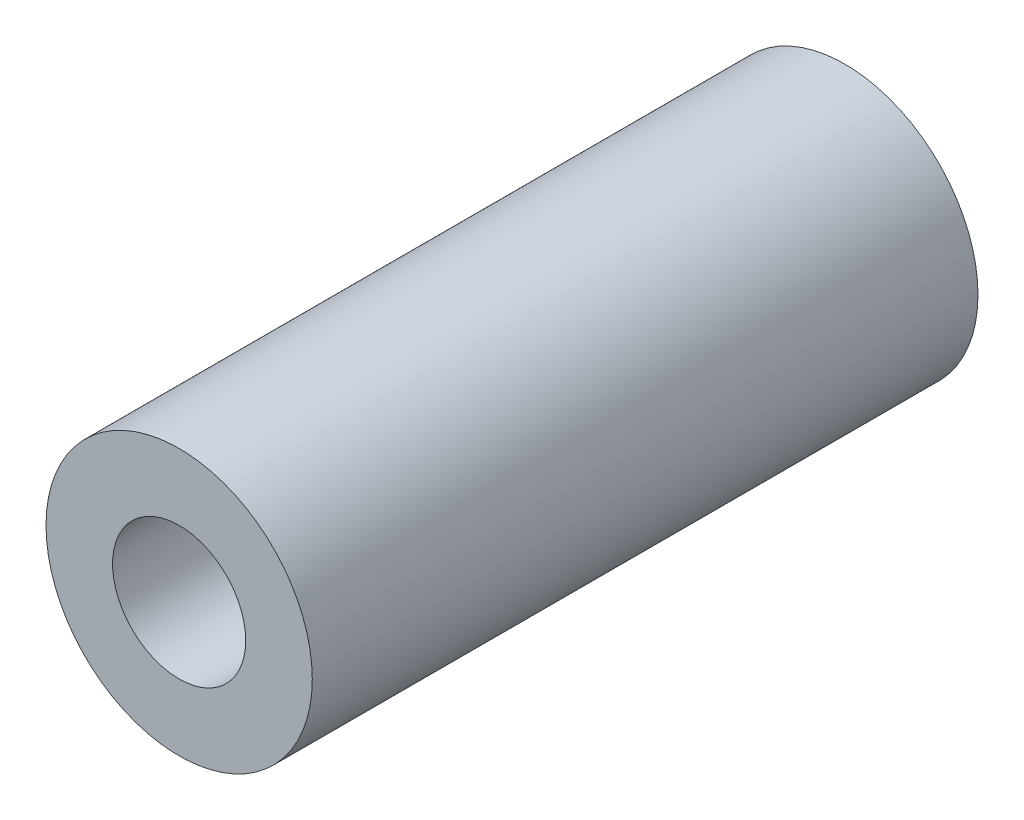
SolidWorks part; units mm, degrees
ref_plane "前视基准面" through (0, 0, 0) normal (0, 0, 1) x (1, 0, 0)
ref_plane "上视基准面" through (0, 0, 0) normal (0, 1, 0) x (1, 0, 0)
ref_plane "右视基准面" through (0, 0, 0) normal (1, 0, 0) x (0, 0, -1)
other "Configuration Table"
sketch "草图1" plane through (0, 0, 0) normal (0, 0, 1) x (1, 0, 0)
  circle A0 centre (0, 0) radius 5
  circle A1 centre (0, 0) radius 10
  dimension "D1" = 10
  dimension "D2" = 20
extrude "凸台-拉伸1" add sketch "草图1" along normal blind 50
